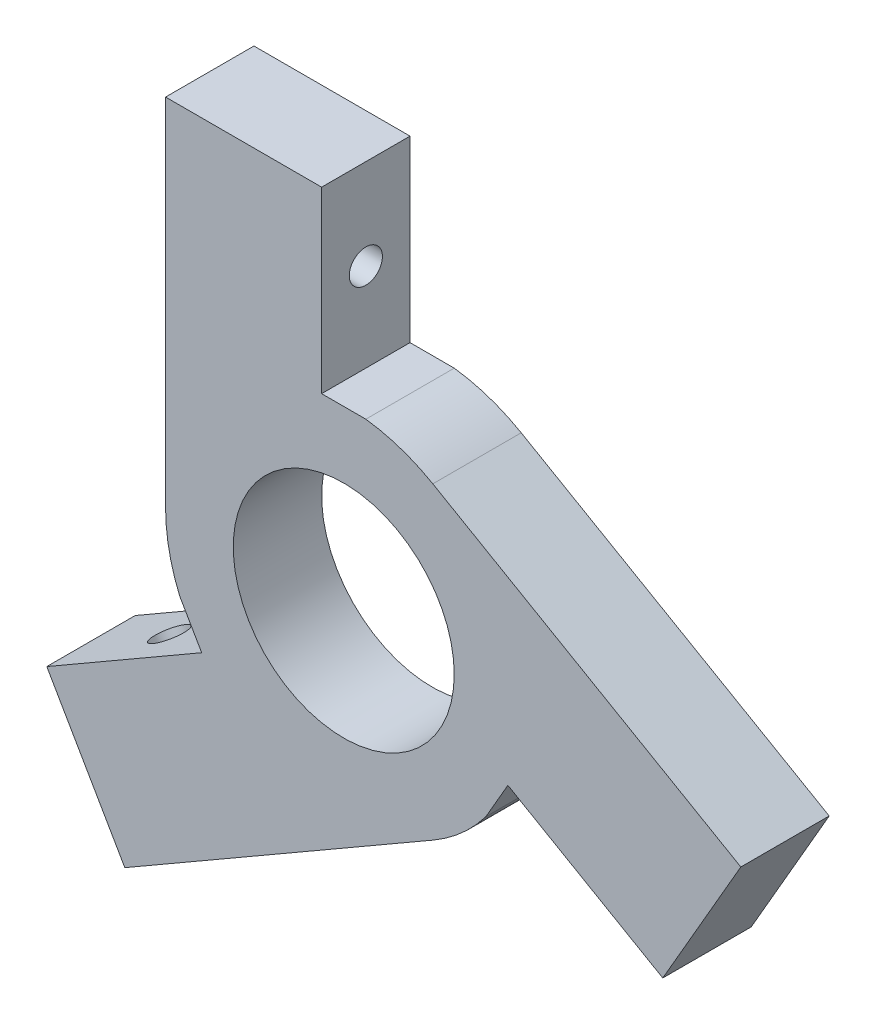
SolidWorks part; units mm, degrees
material "ASTM A36 Steel"
ref_plane "Front Plane" through (0, 0, 0) normal (0, 0, 1) x (1, 0, 0)
ref_plane "Top Plane" through (0, 0, 0) normal (0, 1, 0) x (1, 0, 0)
ref_plane "Right Plane" through (0, 0, 0) normal (1, 0, 0) x (0, 0, -1)
sketch "Sketch1" plane through (0, 0, 0) normal (0, 0, 1) x (1, 0, 0)
  line L0 (-114.3, 0) -> (114.3, 0) construction
  line L1 (0, -114.3) -> (0, 114.3) construction
  line L2 (-91.2245, -114.3) -> (91.2245, -114.3) construction
  line L3 (-130.0545, 114.3) -> (6.35, 114.3) construction
  line L4 (114.3, -89.022) -> (114.3, 89.022) construction
  line L5 (-114.3, -82.9481) -> (-114.3, 82.9481) construction
  line L6 (0, 114.3) -> (6.35, 114.3) construction
  line L7 (-39.1006, 50.8) -> (39.1006, 50.8) construction
  line L8 (-6.35, 50.8) -> (6.35, 50.8) construction
  line L9 (6.35, 50.8) -> (6.35, 114.3) construction
  line L10 (-6.35, 50.8) -> (-6.35, 114.3) construction
  line L11 (-6.35, 114.3) -> (6.35, 114.3) construction
  line L12 (6.35, 114.3) -> (14.695, 105.955) construction
  line L13 (6.35, 97.6099) -> (14.695, 105.955) construction
  line L14 (6.35, 97.6099) -> (6.35, 50.8) construction
  line L15 (36.2702, 114.3) -> (130.0545, 114.3) construction
  line L16 (81.3577, -54.3042) -> (40.8191, -30.8993) construction
  line L17 (47.1691, -19.9007) -> (40.8191, -30.8993) construction
  line L18 (47.1691, -19.9007) -> (102.1617, -51.6507) construction
  line L19 (81.3577, -54.3042) -> (84.4122, -65.7038) construction
  line L20 (95.8117, -62.6493) -> (84.4122, -65.7038) construction
  line L21 (102.1617, -51.6507) -> (95.8117, -62.6493) construction
  line L22 (-87.7077, -43.3057) -> (-47.1691, -19.9007) construction
  line L23 (-40.8191, -30.8993) -> (-47.1691, -19.9007) construction
  line L24 (-40.8191, -30.8993) -> (-95.8117, -62.6493) construction
  line L25 (-87.7077, -43.3057) -> (-99.1072, -40.2512) construction
  line L26 (-102.1617, -51.6507) -> (-99.1072, -40.2512) construction
  line L27 (-95.8117, -62.6493) -> (-102.1617, -51.6507) construction
  line L28 (-6.35, 63.5) -> (6.35, 63.5) construction
  line L29 (58.1676, -26.2507) -> (51.8176, -37.2493) construction
  line L30 (-51.8176, -37.2493) -> (-58.1676, -26.2507) construction
  line L31 (-51.1953, 0) -> (-51.1953, 102.1936)
  line L32 (-51.1953, 102.1936) -> (-6.35, 102.1936)
  line L33 (-6.35, 102.1936) -> (-6.35, 50.8)
  line L34 (-6.35, 50.8) -> (6.35, 50.8)
  line L35 (114.0999, -6.7603) -> (91.6772, -45.5975)
  line L36 (25.5977, 44.3365) -> (114.0999, -6.7603)
  line L37 (91.6772, -45.5975) -> (47.1691, -19.9007)
  line L38 (47.1691, -19.9007) -> (40.8191, -30.8993)
  line L39 (-62.9046, -95.4333) -> (-85.3272, -56.5961)
  line L40 (25.5977, -44.3365) -> (-62.9046, -95.4333)
  line L41 (-85.3272, -56.5961) -> (-40.8191, -30.8993)
  line L42 (-40.8191, -30.8993) -> (-47.1691, -19.9007)
  circle A0 centre (0, 0) radius 31.75
  circle A1 centre (0, 0) radius 114.3 construction
  circle A2 centre (0, 0) radius 50.8 construction
  arc A3 (-51.1953, 0) -> (-47.1691, -19.9007) centre (0, 0) ccw
  arc A4 (25.5977, 44.3365) -> (6.35, 50.8) centre (0, 0) ccw
  arc A5 (25.5977, -44.3365) -> (40.8191, -30.8993) centre (0, 0) ccw
  point P4 (0, 0)
  point P8 (0, 0)
  point P14 (0, -114.3)
  point P19 (0, 114.3)
  point P20 (114.3, 0)
  point P23 (-114.3, 0)
  point P27 (0, 50.8)
  point P30 (0, 50.8)
  point P49 (0, 0)
  point P51 (0, 63.5)
  point P58 (0, 0)
  point P72 (0, 0)
  dimension "D1" = 63.5
  dimension "D2" = 228.6
  dimension "D3" = 228.6
  dimension "D4" = 228.6
  dimension "D5" = 114.3
  dimension "D6" = 50.8
  dimension "D7" = 12.7
  dimension "D8" = 45
  dimension "D9" = 45
  dimension "D11" = 12.7
  dimension "D13" = 3
  dimension "D10" = 3
  dimension "D12" = 3
extrude "Boss-Extrude1" add sketch "Sketch1" along normal mid plane 25.4
sketch "Sketch2" plane through (-6.35, 0, 0) normal (1, 0, 0) x (0, 0, -1)
  line L0 (-143.3226, 0) -> (143.3226, 0) construction
  line L1 (0, -124.3205) -> (0, 124.3205) construction
  line L2 (-12.7, 50.8) -> (12.7, 50.8) construction
  circle A0 centre (0, 76.2) radius 4.7625
  point P4 (0, 0)
  point P8 (0, 0)
  dimension "D2" = 9.525
  dimension "D1" = 25.4
extrude "Cut-Extrude1" cut sketch "Sketch2" against normal blind 25.4
pattern_circular "CirPattern1" count 3 over 360 about axis through (0, 0, 0) along (0, 0, 1) of "Cut-Extrude1"
thread "Thread1" pitch 1.0583 start angle 0, offset 0, length 25.4, pitch 1.0583, diameter 9.525
ref_plane "Plane1" through (-6.35, 76.2, 4.7625) normal (0, -1, 0) x (0, 0, 1)
sketch "Thread Profile1" plane through (-6.35, 76.2, 4.7625) normal (0, -1, 0) x (0, 0, 1)
  line L0 (0, 0) -> (0, 1.0583) construction
  line L1 (0, 0) -> (0.5728, 0.3307)
  line L2 (0.5728, 0.3307) -> (0.5728, 0.463)
  line L3 (0.5728, 0.463) -> (0, 0.7937)
  line L4 (0.5728, 0.3969) -> (0, 0.3969) construction
  line L11 (0, 0) -> (0, 0.7937)
  point P2 (0, 0)
  dimension "Pitch" = 1.0583
  dimension "Profile_Angle" = 60
  dimension "Profile_Land" = 0.1323
  dimension "Profile_Height" = 0.5728
thread "Thread2" pitch 1.0583 start angle 0, offset 0, length 25.4, pitch 1.0583, diameter 9.525
ref_plane "Plane2" through (73.2906, -34.982, 0) normal (0, 0, 1) x (0.866, -0.5, 0)
sketch "Thread Profile2" plane through (73.2906, -34.982, 0) normal (0, 0, 1) x (0.866, -0.5, 0)
  line L0 (0, 0) -> (0, 1.0583) construction
  line L1 (0, 0) -> (0.5728, 0.3307)
  line L2 (0.5728, 0.3307) -> (0.5728, 0.463)
  line L3 (0.5728, 0.463) -> (0, 0.7937)
  line L4 (0.5728, 0.3969) -> (0, 0.3969) construction
  line L11 (0, 0) -> (0, 0.7937)
  point P2 (0, 0)
  dimension "Pitch" = 1.0583
  dimension "Profile_Angle" = 60
  dimension "Profile_Land" = 0.1323
  dimension "Profile_Height" = 0.5728
thread "Thread3" pitch 1.0583 start angle 0, offset 0, length 25.4, pitch 1.0583, diameter 9.525
ref_plane "Plane3" through (-66.9406, -45.9805, 0) normal (0, 0, 1) x (-0.866, -0.5, 0)
sketch "Thread Profile3" plane through (-66.9406, -45.9805, 0) normal (0, 0, 1) x (-0.866, -0.5, 0)
  line L0 (0, 0) -> (0, 1.0583) construction
  line L1 (0, 0) -> (0.5728, 0.3307)
  line L2 (0.5728, 0.3307) -> (0.5728, 0.463)
  line L3 (0.5728, 0.463) -> (0, 0.7937)
  line L4 (0.5728, 0.3969) -> (0, 0.3969) construction
  line L11 (0, 0) -> (0, 0.7937)
  point P2 (0, 0)
  dimension "Pitch" = 1.0583
  dimension "Profile_Angle" = 60
  dimension "Profile_Land" = 0.1323
  dimension "Profile_Height" = 0.5728
